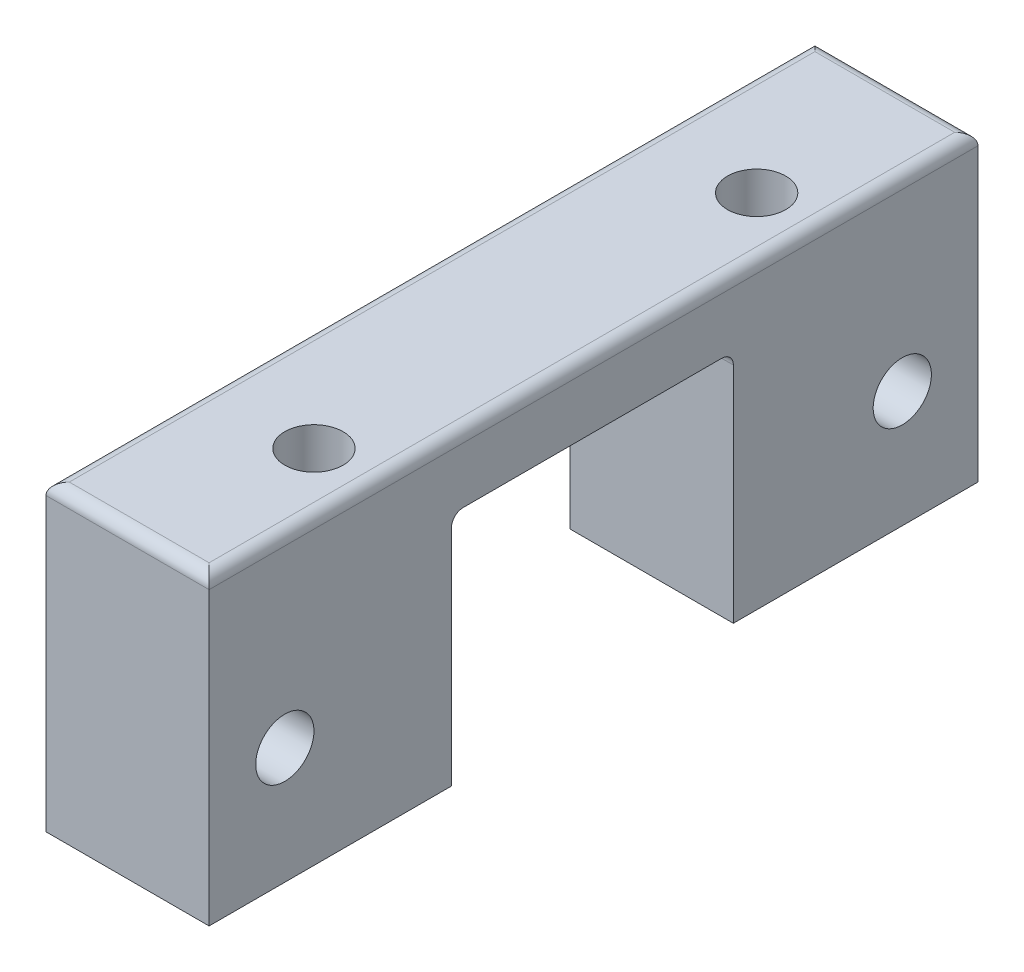
SolidWorks part; units mm, degrees
ref_plane "Front Plane" through (0, 0, 0) normal (0, 0, 1) x (1, 0, 0)
ref_plane "Top Plane" through (0, 0, 0) normal (0, 1, 0) x (1, 0, 0)
ref_plane "Right Plane" through (0, 0, 0) normal (1, 0, 0) x (0, 0, -1)
sketch "Sketch1" plane through (0, 0, 0) normal (0, 1, 0) x (1, 0, 0)
  line L1 (-3.5, -16.5) -> (3.5, -16.5)
  line L2 (-3.5, -16.5) -> (-3.5, 16.5)
  line L3 (-3.5, 16.5) -> (3.5, 16.5)
  line L4 (3.5, -16.5) -> (3.5, 16.5)
  line L5 (-3.5, -16.5) -> (3.5, 16.5) construction
  line L6 (-3.5, 16.5) -> (3.5, -16.5) construction
  point P0 (0, 0)
  dimension "D1" = 7
  dimension "D2" = 33
extrude "Boss-Extrude1" add sketch "Sketch1" along normal blind 13 contours L2 L1 L4 L3
fillet "Fillet4" radius 0.5 4 edges at (3.5, 13, 0) (-3.5, 13, 0) (0, 13, 16.5) (0, 13, -16.5)
sketch "Sketch3" plane through (0, 13, 0) normal (0, 1, 0) x (1, 0, 0)
  line L0 (0, 42.8928) -> (0, -43.8424) construction
  line L1 (1, 42.8928) -> (1, -43.8424) construction
  line L2 (-39.1903, 0) -> (48.372, 0) construction
  line L3 (-39.1903, 9.5) -> (68.2717, 9.5) construction
  circle A0 centre (1, 9.5) radius 1.25
  circle A1 centre (1, -9.5) radius 1.25
  dimension "D3" = 2.5
  dimension "D1" = 1
  dimension "D2" = 9.5
extrude "Cut-Extrude1" cut sketch "Sketch3" against normal through all contours A0 | A1
sketch "Sketch5" plane through (-3.5, 0, 0) normal (-1, 0, 0) x (0, 0, 1)
  line L0 (-16.5, 12.5) -> (-16.5, 0) construction
  line L1 (16.5, 12.5) -> (16.5, 0) construction
  line L3 (-6, 23.6969) -> (-6, -8.9939) construction
  line L4 (6.1, -8.9939) -> (6.1, 23.6969) construction
  line L5 (16.5, 0) -> (-16.5, 0) construction
  line L6 (-6, 0) -> (6.1, 0)
  line L7 (-6, 0) -> (-6, 10.1)
  line L8 (-6, 10.1) -> (6.1, 10.1)
  line L9 (6.1, 0) -> (6.1, 10.1)
  line L10 (0, 21.3823) -> (0, -12.7084) construction
  line L11 (-28.3473, 5) -> (25.8355, 5) construction
  line L12 (16.5, 0) -> (-16.5, 0) construction
  line L13 (-13.25, 24.7968) -> (-13.25, -15.043) construction
  line L14 (11.25, 24.7968) -> (11.25, -15.043) construction
  circle A0 centre (-13.25, 5) radius 1.25
  circle A2 centre (13.25, 5) radius 1.25
  circle A3 centre (0, 5) radius 3.3 construction
  circle A4 centre (13.25, 5) radius 9.95 construction
  circle A5 centre (-13.25, 5) radius 9.95 construction
  dimension "D9" = 2.5
  dimension "D7" = 6.6
  dimension "D8" = 19.9
  dimension "D10" = 6
  dimension "D11" = 2.5
  dimension "D1" = 12.1
  dimension "D2" = 33
  dimension "D3" = 10.5
  dimension "D4" = 10.1
  dimension "D5" = 10.4
  dimension "D6" = 5
extrude "Cut-Extrude2" cut sketch "Sketch5" against normal through all
fillet "Fillet5" radius 0.5 2 edges at (0, 10.1, -6) (0, 10.1, 6.1)
